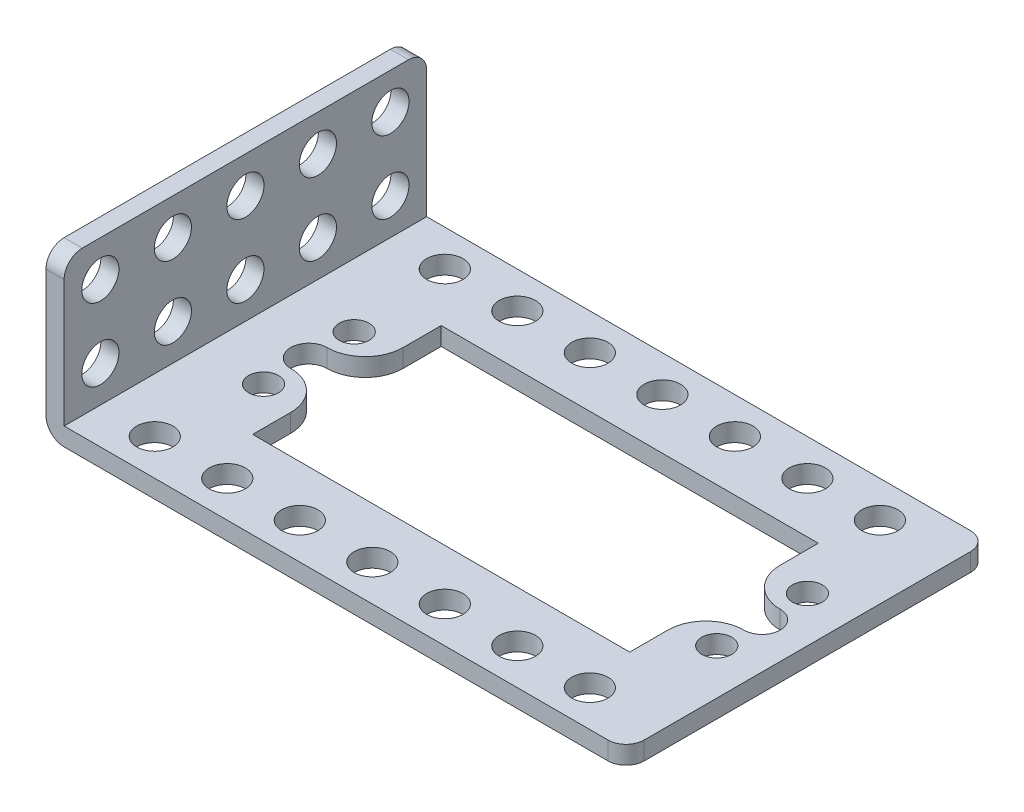
SolidWorks part; units mm, degrees
ref_plane "Front Plane" through (0, 0, 0) normal (0, 0, 1) x (1, 0, 0)
ref_plane "Top Plane" through (0, 0, 0) normal (0, 1, 0) x (1, 0, 0)
ref_plane "Right Plane" through (0, 0, 0) normal (1, 0, 0) x (0, 0, -1)
sketch "Sketch1" plane through (0, 0, 0) normal (0, 1, 0) x (1, 0, 0)
  line L1 (0, 0) -> (64, 0)
  line L2 (0, 0) -> (0, 40)
  line L3 (0, 40) -> (64, 40)
  line L4 (64, 0) -> (64, 40)
  dimension "D1" = 64
  dimension "D2" = 40
extrude "Boss-Extrude1" add sketch "Sketch1" along normal blind 2
sketch "Sketch2" plane through (0, 2, 0) normal (0, 1, 0) x (1, 0, 0)
  line L0 (64, 40) -> (0, 40) construction
  line L1 (0, 0) -> (2, 0)
  line L2 (0, 0) -> (0, 40)
  line L3 (0, 40) -> (2, 40)
  line L4 (2, 0) -> (2, 40)
  dimension "D1" = 2
extrude "Boss-Extrude2" add sketch "Sketch2" along normal blind 16
sketch "Sketch3" plane through (0, 2, 0) normal (0, 1, 0) x (1, 0, 0)
  line L0 (0, 40) -> (0, 0) construction
  line L2 (64, 40) -> (2, 40) construction
  circle A0 centre (8, 36) radius 2
  dimension "D1" = 4
  dimension "D2" = 8
  dimension "D3" = 4
extrude "Cut-Extrude1" cut sketch "Sketch3" against normal through all
pattern_linear "LPattern1" count 7 spacing 8 along (1, 0, 0) of "Cut-Extrude1"
ref_plane "Plane1" through (0, 0, -20) normal (0, 0, -1) x (-1, 0, 0)
mirror "Mirror1" about plane through (0, 0, -20) normal (0, 0, -1) of "LPattern1", "Cut-Extrude1"
sketch "Sketch4" plane through (0, 2, 0) normal (0, 1, 0) x (1, 0, 0)
  line L1 (13.2, 30.4) -> (54.8, 30.4)
  line L2 (13.2, 30.4) -> (13.2, 26.2)
  line L3 (13.2, 9.6) -> (54.8, 9.6)
  line L4 (54.8, 30.4) -> (54.8, 26.2)
  line L5 (64, 0) -> (64, 40) construction
  line L6 (9.9, 20) -> (-9.9, 20) construction
  line L7 (13.2, 13.8) -> (13.2, 9.6)
  line L8 (34, 30.4) -> (34, 9.6) construction
  line L9 (54.8, 13.8) -> (54.8, 9.6)
  arc A0 (13.2, 13.8) -> (9, 18) centre (9, 13.8) ccw
  arc A1 (9, 18) -> (9, 22) centre (9, 20) cw
  arc A2 (9, 22) -> (13.2, 26.2) centre (9, 26.2) ccw
  arc A3 (54.8, 13.8) -> (59, 18) centre (59, 13.8) cw
  arc A4 (59, 18) -> (59, 22) centre (59, 20) ccw
  arc A5 (59, 22) -> (54.8, 26.2) centre (59, 26.2) cw
  point P7 (34, 30.4)
  dimension "D5" = 2
  dimension "D1" = 20.8
  dimension "D2" = 41.6
  dimension "D4" = 30
  dimension "D6" = 25
extrude "Cut-Extrude2" cut sketch "Sketch4" against normal through all contours L1 L4 A5 A4 A3 L9 L3 L7 A0 A1 A2 L2
hole_wizard "Tap Drill for M4x0.7 Tap1" positions "Sketch5" profile "Sketch6" hole size "M4x0.7" standard "ANSI Metric"
sketch "Sketch5" plane through (0, 2, 0) normal (0, 1, 0) x (1, 0, 0)
  line L0 (13.2, 30.4) -> (54.8, 30.4) construction
  line L1 (9.9, 20) -> (-9.9, 20) construction
  point P0 (9, 25)
  point P2 (9, 15)
  point P4 (59, 15)
  point P6 (59, 25)
  point P21 (34, 30.4)
  dimension "D1" = 10
  dimension "D2" = 50
  dimension "D3" = 25
  dimension "D4" = 5
sketch "Sketch6" plane through (9, 2, -25) normal (1, 0, 0) x (0, 0, 1)
  line L0 (0, 0) -> (0, 10.76)
  line L1 (0, 10.76) -> (1.65, 10.76)
  line L2 (1.65, 10.76) -> (1.65, 0)
  line L5 (1.65, 0) -> (0, 0)
  line L10 (0, 10.76) -> (-1.65, 10.76) construction
  line L11 (0, -6.35) -> (0, 107.95) construction
  dimension "Hole Dia." = 3.3
  dimension "Hole Depth" = 10.76
  dimension "Drill Angle" = 180
sketch "Sketch7" plane through (2, 0, 0) normal (1, 0, 0) x (0, 0, -1)
  line L0 (0, 18) -> (40, 18) construction
  line L1 (0, 18) -> (0, 2) construction
  circle A0 centre (4, 14) radius 2.05
  dimension "D1" = 4.1
  dimension "D2" = 4
  dimension "D3" = 4
extrude "Cut-Extrude3" cut sketch "Sketch7" against normal through all
pattern_linear "LPattern2" count 5 spacing 8 along (0, 0, -1) count 2 spacing 8 along (0, -1, 0) of "Cut-Extrude3"
fillet "Fillet1" radius 2 5 edges at (0, 0, -20) (64, 1, 0) (64, 1, -40) (1, 18, -40) (1, 18, 0)
